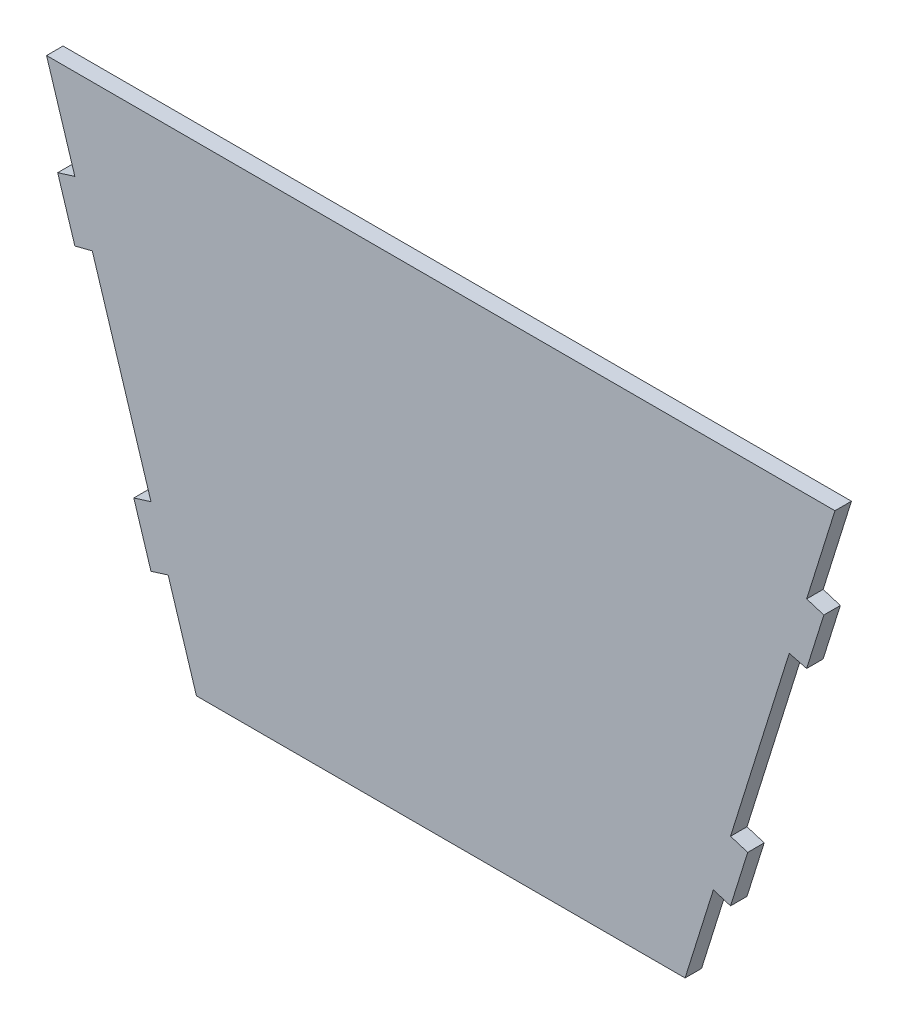
SolidWorks part; units mm, degrees
ref_plane "Front Plane" through (0, 0, 0) normal (0, 0, 1) x (1, 0, 0)
ref_plane "Top Plane" through (0, 0, 0) normal (0, 1, 0) x (1, 0, 0)
ref_plane "Right Plane" through (0, 0, 0) normal (1, 0, 0) x (0, 0, -1)
sketch "Sketch2" plane through (0, 0, 0) normal (0, 0, 1) x (1, 0, 0)
  line L0 (-40.75, 0) -> (40.75, 0)
  line L1 (55, 0) -> (-55, 0) construction
  line L2 (40.75, 0) -> (45.4687, 15.1)
  line L3 (65.75, 80) -> (-65.75, 80)
  line L4 (0, -55) -> (0, 55) construction
  line L5 (-40.75, 0) -> (-45.4687, 15.1)
  line L7 (61.0312, 64.9) -> (63.8947, 64.0052)
  line L8 (58.1231, 55.5938) -> (61.0277, 54.8433)
  line L9 (63.8947, 64.0052) -> (61.0277, 54.8433)
  line L11 (45.4687, 15.1) -> (48.3322, 14.2052)
  line L12 (48.3322, 24.263) -> (51.1956, 23.3682)
  line L13 (48.3322, 14.2052) -> (51.1956, 23.3682)
  line L14 (-48.3322, 14.2052) -> (-51.1956, 23.3682)
  line L15 (-48.3322, 24.263) -> (-51.1956, 23.3682)
  line L16 (-45.4687, 15.1) -> (-48.3322, 14.2052)
  line L18 (-63.8947, 64.0052) -> (-61.0277, 54.8433)
  line L19 (-58.1231, 55.5938) -> (-61.0277, 54.8433)
  line L20 (-61.0312, 64.9) -> (-63.8947, 64.0052)
  line L22 (-61.0312, 64.9) -> (-65.75, 80)
  line L23 (-48.3322, 24.263) -> (-58.1231, 55.5938)
  line L24 (48.3322, 24.263) -> (58.1231, 55.5938)
  line L25 (61.0312, 64.9) -> (65.75, 80)
  point P11 (0, 0)
  point P12 (0, 80)
  dimension "D2" = 81.5
  dimension "D3" = 25
  dimension "D1" = 80
  dimension "D4" = 15.1
  dimension "D5" = 3
  dimension "incert_length" = 9.6
  dimension "D7" = 9.6
  dimension "D8" = 3
  dimension "D6" = 15.1
extrude "Boss-Extrude1" add sketch "Sketch2" along normal blind 2.75 contours L5 L0 L2 L3
equation "\"incert_length\"=9.6"
equation "\"incert_length@Sketch2\"=\"incert_length\""
equation "\"D7@Sketch2\"=\"incert_length\""
equation "\"incert_width\"=3"
equation "\"D5@Sketch2\"=\"incert_width\""
equation "\"D8@Sketch2\"=\"incert_width\""
equation "\"incert_offset\"=15.1"
equation "\"D4@Sketch2\"=\"incert_offset\""
equation "\"D6@Sketch2\"=\"incert_offset\""
